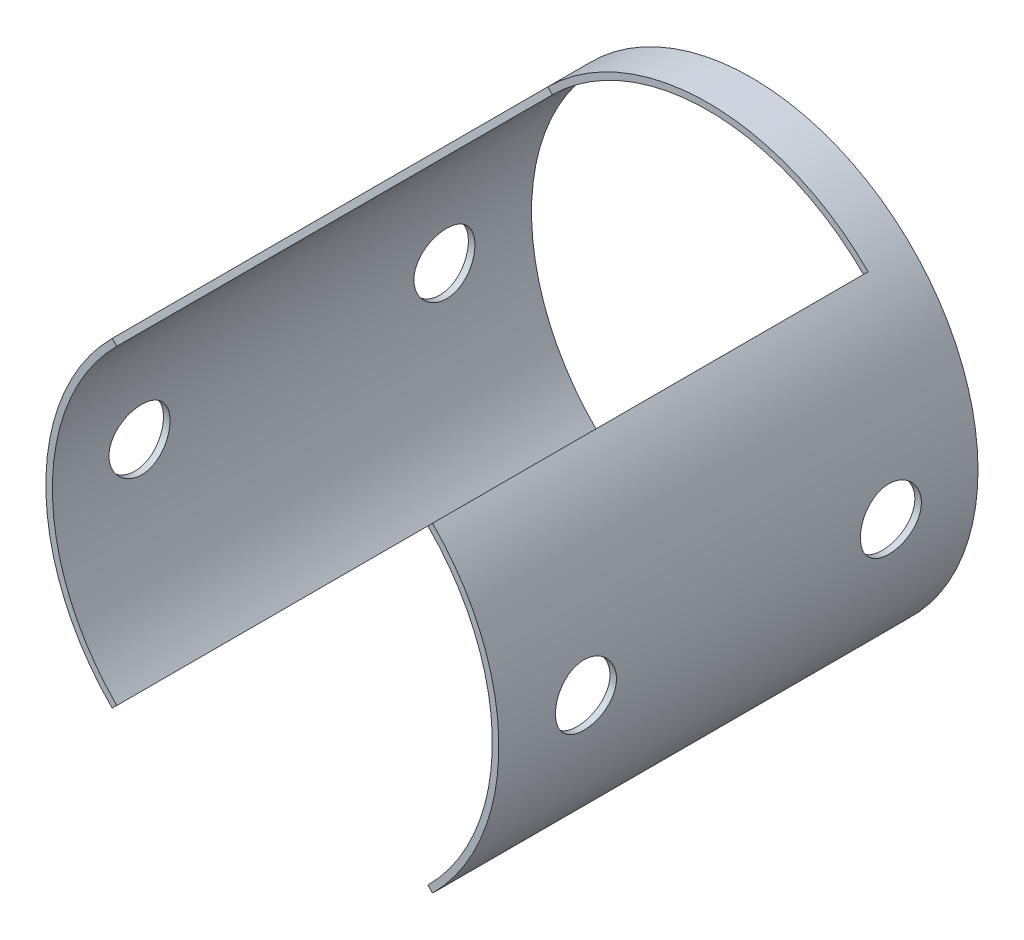
SolidWorks part; units mm, degrees
ref_plane "Front Plane" through (0, 0, 0) normal (0, 0, 1) x (1, 0, 0)
ref_plane "Top Plane" through (0, 0, 0) normal (0, 1, 0) x (1, 0, 0)
ref_plane "Right Plane" through (0, 0, 0) normal (1, 0, 0) x (0, 0, -1)
sketch "Sketch2" plane through (0, 0, 0) normal (0, 0, 1) x (1, 0, 0)
  circle A0 centre (0, 0) radius 26
  circle A1 centre (0, 0) radius 25.25
  dimension "D1" = 52
  dimension "D2" = 50.5
extrude "Boss-Extrude1" add sketch "Sketch2" along normal blind 5
sketch "Sketch3" plane through (0, 0, 5) normal (0, 0, 1) x (1, 0, 0)
  line L0 (0, 8.746) -> (0, -8.9113) construction
  line L1 (-9.1237, 0) -> (9.2654, 0) construction
  line L2 (-17.8544, 17.8544) -> (-18.3848, 18.3848)
  line L4 (-17.8544, -17.8544) -> (-18.3848, -18.3848)
  line L5 (17.8544, -17.8544) -> (18.3848, -18.3848)
  line L6 (17.8544, 17.8544) -> (18.3848, 18.3848)
  circle A0 centre (0, 0) radius 26 construction
  arc A1 (-18.3848, 18.3848) -> (-18.3848, -18.3848) centre (0, 0) ccw
  circle A2 centre (0, 0) radius 25.25 construction
  arc A3 (-17.8544, -17.8544) -> (-17.8544, 17.8544) centre (0, 0) cw
  arc A4 (18.3848, 18.3848) -> (18.3848, -18.3848) centre (0, 0) cw
  arc A5 (17.8544, -17.8544) -> (17.8544, 17.8544) centre (0, 0) ccw
  dimension "D1" = 45
extrude "Boss-Extrude2" add sketch "Sketch3" along normal blind 50
sketch "Sketch4" plane through (0, 0, 0) normal (1, 0, 0) x (0, 0, -1)
  line L0 (-55, 18.3848) -> (-55, -18.3848) construction
  circle A0 centre (-45, 0) radius 3.5
  circle A1 centre (-10, 0) radius 3.5
  dimension "D1" = 7
  dimension "D3" = 7
  dimension "D2" = 10
  dimension "D4" = 10
extrude "Cut-Extrude1" cut sketch "Sketch4" against normal through all both and the other way through all
